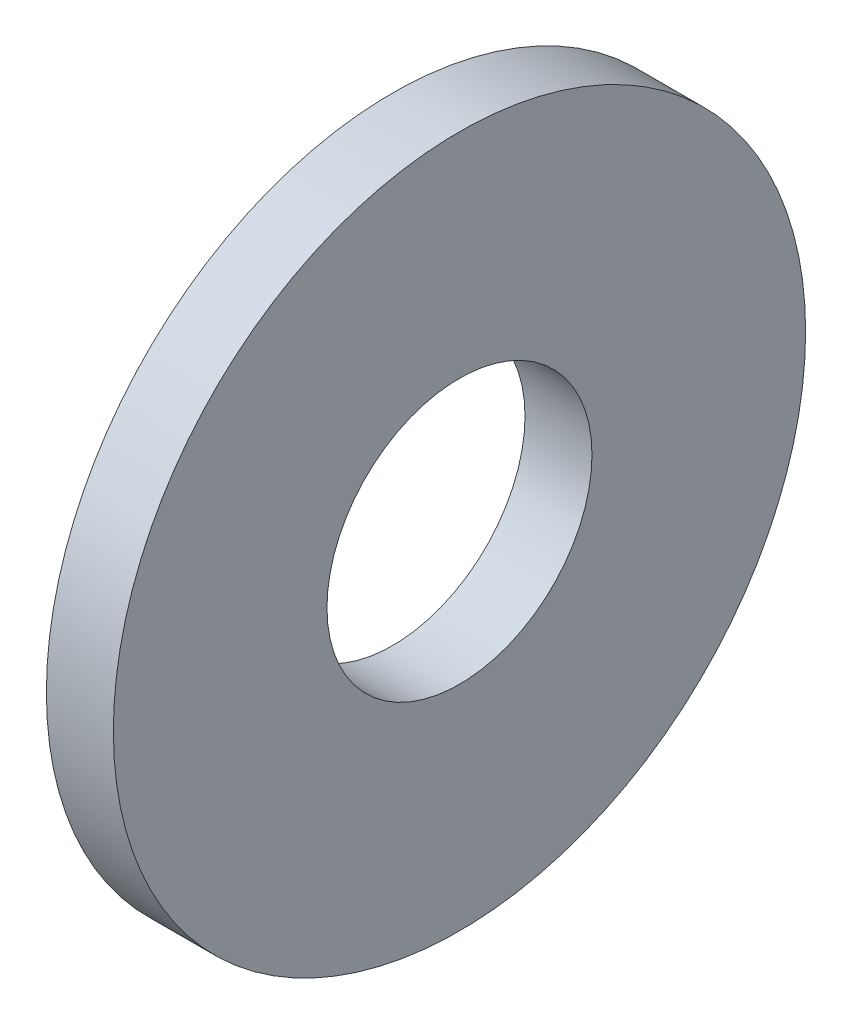
SolidWorks part; units mm, degrees
material "Alumina"
ref_plane "Front Plane" through (0, 0, 0) normal (0, 0, 1) x (1, 0, 0)
ref_plane "Top Plane" through (0, 0, 0) normal (0, 1, 0) x (1, 0, 0)
ref_plane "Right Plane" through (0, 0, 0) normal (1, 0, 0) x (0, 0, -1)
sketch "Sketch1" plane through (0, 0, 0) normal (1, 0, 0) x (0, 0, -1)
  circle A0 centre (0, 0) radius 3.5687
  circle A1 centre (0, 0) radius 9.3218
  dimension "OD" = 7.1374
  dimension "ID" = 18.6436
extrude "Boss-Extrude1" add sketch "Sketch1" along normal blind 1.8034
